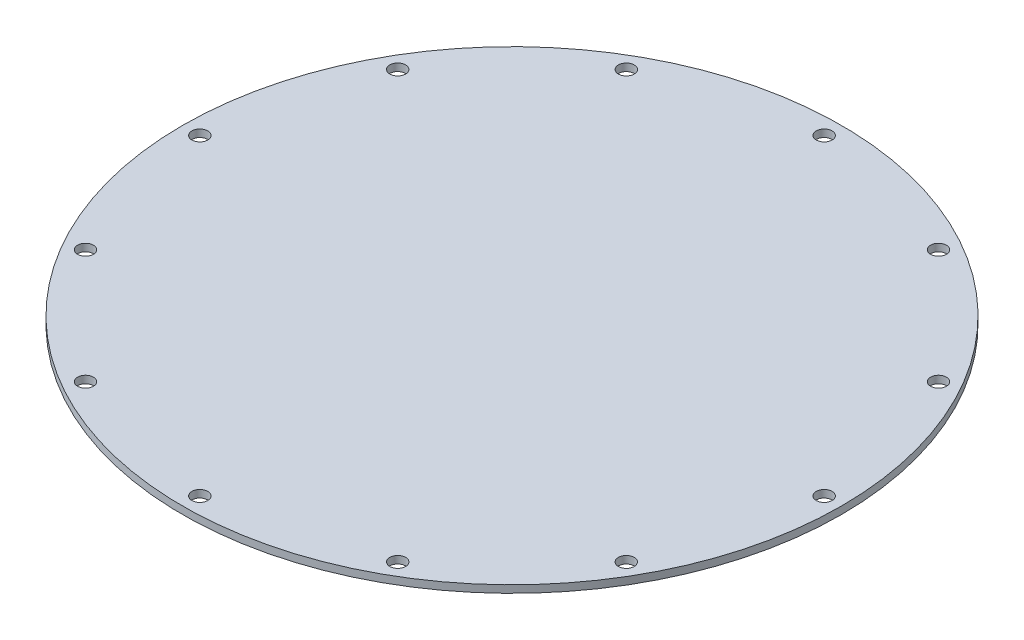
SolidWorks part; units mm, degrees
material "Hexcel AS4C (3000 Filaments)"
ref_plane "Front Plane" through (0, 0, 0) normal (0, 0, 1) x (1, 0, 0)
ref_plane "Top Plane" through (0, 0, 0) normal (0, 1, 0) x (1, 0, 0)
ref_plane "Right Plane" through (0, 0, 0) normal (1, 0, 0) x (0, 0, -1)
sketch "Sketch1" plane through (0, 0, 0) normal (0, 0, 1) x (1, 0, 0)
  line L0 (0, 20.465) -> (0, 18.965) construction
  line L1 (0, 20.465) -> (-66.5, 20.465) construction
  line L2 (0, 18.965) -> (-66.5, 18.965) construction
  line L3 (-66.5, 20.465) -> (-66.5, 18.965) construction
  line L4 (0, 20.465) -> (0, 18.965)
  line L5 (0, 20.465) -> (-66.5, 20.465)
  line L6 (0, 18.965) -> (-66.5, 18.965)
  line L7 (-66.5, 20.465) -> (-66.5, 18.965)
revolve "Revolve1" add sketch "Sketch1" angle 360 about L4
sketch "Sketch7" plane through (0, 20.465, 0) normal (0, 1, 0) x (1, 0, 0)
  circle A1 centre (0, 63) radius 1.6
  circle A2 centre (0, 63) radius 1.6
  dimension "D1" = 0
extrude "Cut-Extrude1" cut sketch "Sketch7" against normal through all
pattern_circular "CirPattern2" count 12 over 360 about axis through (0, 0, 0) along (0, 1, 0) of "Cut-Extrude1"
